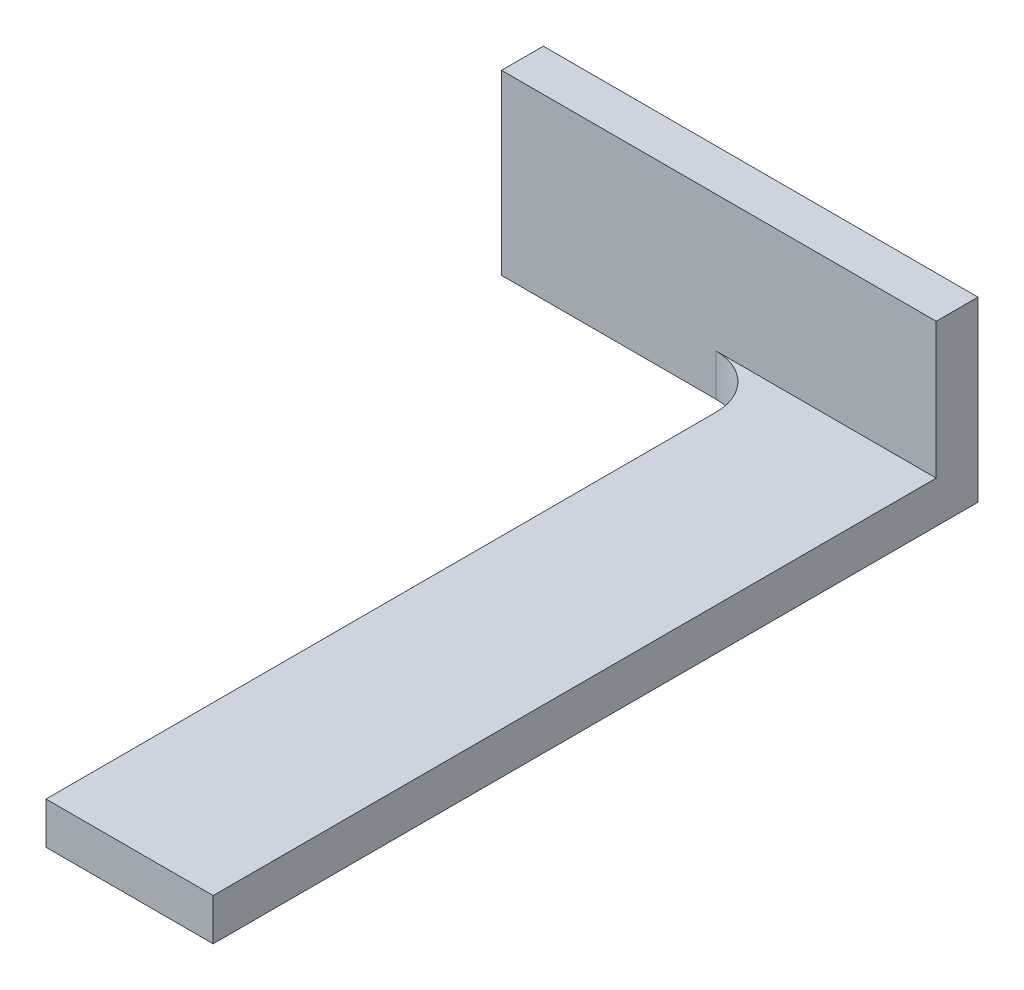
SolidWorks part; units mm, degrees
material "Aluminum Black Anodize"
ref_plane "Front" through (0, 0, 0) normal (0, 0, 1) x (1, 0, 0)
ref_plane "Top" through (0, 0, 0) normal (0, 1, 0) x (1, 0, 0)
ref_plane "Right" through (0, 0, 0) normal (1, 0, 0) x (0, 0, -1)
sketch "Sketch1" plane through (0, 0, 0) normal (0, 0, 1) x (1, 0, 0)
  line L1 (0, 0) -> (52, 0)
  line L2 (0, 0) -> (0, -21.25)
  line L3 (0, -21.25) -> (52, -21.25)
  line L4 (52, 0) -> (52, -21.25)
  dimension "D1" = 52
  dimension "D2" = 21.25
extrude "Extrude1" add sketch "Sketch1" along normal blind 5
sketch "Sketch2" plane through (0, 0, 5) normal (0, 0, 1) x (1, 0, 0)
  line L0 (0, -21.25) -> (52, -21.25) construction
  line L1 (32, -21.25) -> (52, -21.25)
  line L2 (32, -21.25) -> (32, -16.25)
  line L3 (32, -16.25) -> (52, -16.25)
  line L4 (52, -21.25) -> (52, -16.25)
  dimension "D1" = 5
  dimension "D2" = 20
extrude "Extrude2" add sketch "Sketch2" along normal blind 86.5
fillet "Fillet1" radius 6.35 1 edges
